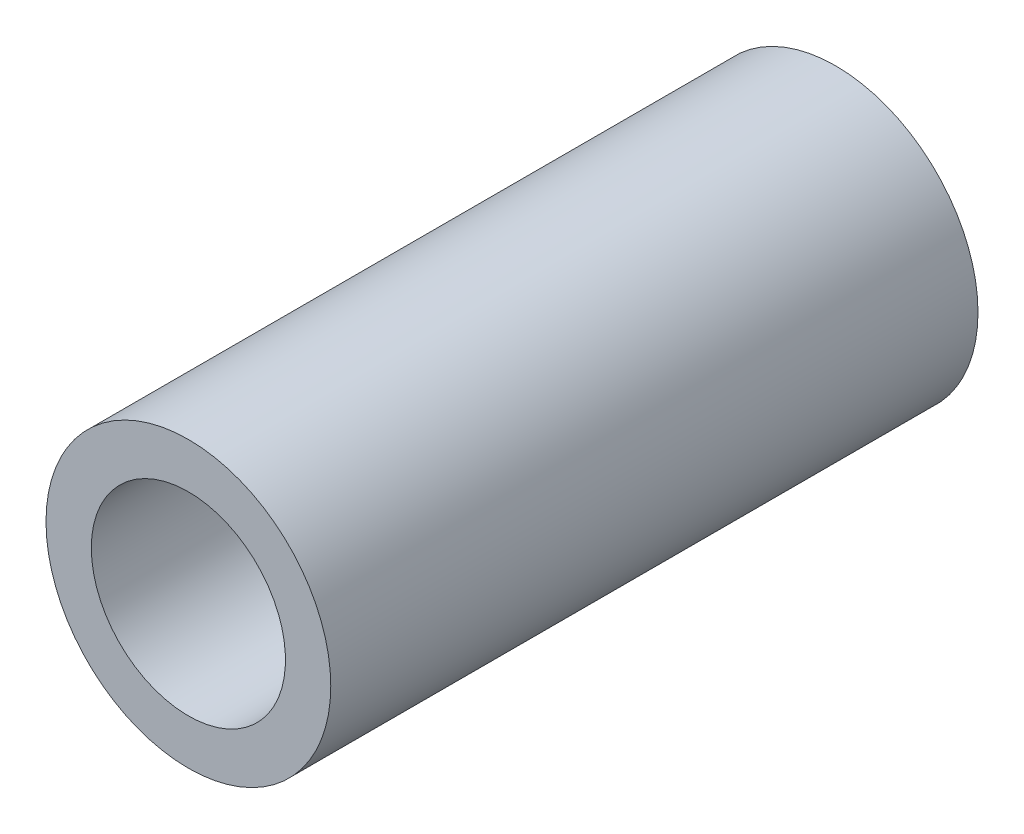
SolidWorks part; units mm, degrees
ref_plane "Plan de face" through (0, 0, 0) normal (0, 0, 1) x (1, 0, 0)
ref_plane "Plan de dessus" through (0, 0, 0) normal (0, 1, 0) x (1, 0, 0)
ref_plane "Plan de droite" through (0, 0, 0) normal (1, 0, 0) x (0, 0, -1)
sketch "Esquisse2" plane through (0, 0, 0) normal (0, 0, 1) x (1, 0, 0)
  circle A0 centre (0, 0) radius 22
extrude "Boss.-Extru.2" add sketch "Esquisse2" along normal blind 100
sketch "Esquisse3" plane through (0, 0, 0) normal (0, 0, -1) x (-1, 0, 0)
  circle A0 centre (0, 0) radius 15
extrude "Enlèv. mat.-Extru.2" cut sketch "Esquisse3" against normal blind 100
